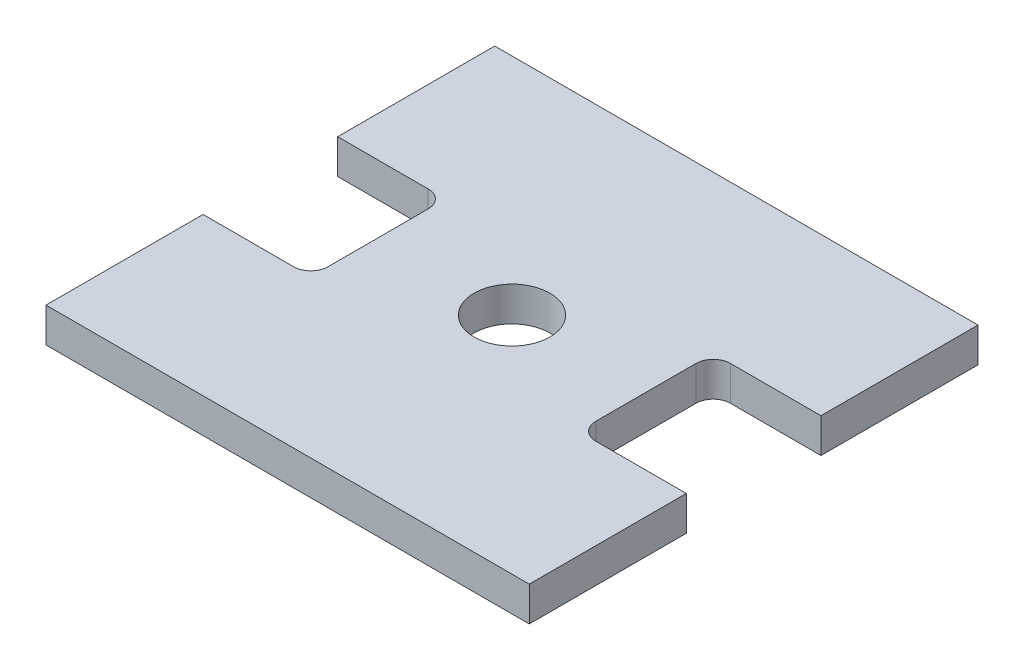
SolidWorks part; units mm, degrees
ref_plane "Спереди" through (0, 0, 0) normal (0, 0, 1) x (1, 0, 0)
ref_plane "Сверху" through (0, 0, 0) normal (0, 1, 0) x (1, 0, 0)
ref_plane "Справа" through (0, 0, 0) normal (1, 0, 0) x (0, 0, -1)
sketch "Эскиз1" plane through (0, 0, 0) normal (0, 1, 0) x (1, 0, 0)
  line L0 (-34.1763, -81.9426) -> (105.8237, 48.0574) construction
  line L1 (-34.1763, 48.0574) -> (105.8237, 48.0574)
  line L2 (-34.1763, 48.0574) -> (-34.1763, 2.5621)
  line L3 (-34.1763, -81.9426) -> (105.8237, -81.9426)
  line L4 (105.8237, 48.0574) -> (105.8237, 2.5621)
  line L5 (-34.1763, 48.0574) -> (105.8237, -81.9426) construction
  line L6 (35.8237, -16.9426) -> (135.9029, -16.9426) construction
  line L7 (-34.1763, -36.4474) -> (-7.9539, -36.4474)
  line L8 (-2.9539, -2.4379) -> (-2.9539, -31.4474)
  line L9 (-34.1763, 2.5621) -> (-7.9539, 2.5621)
  line L10 (-34.1763, -36.4474) -> (-34.1763, -81.9426)
  line L11 (35.8237, -16.9426) -> (35.8237, 51.4154) construction
  line L12 (105.8237, -36.4474) -> (79.6013, -36.4474)
  line L13 (74.6013, -2.4379) -> (74.6013, -31.4474)
  line L14 (105.8237, 2.5621) -> (79.6013, 2.5621)
  line L15 (105.8237, -36.4474) -> (105.8237, -81.9426)
  circle A0 centre (35.8237, -16.9426) radius 11
  arc A1 (-2.9539, -2.4379) -> (-7.9539, 2.5621) centre (-7.9539, -2.4379) ccw
  arc A2 (-7.9539, -36.4474) -> (-2.9539, -31.4474) centre (-7.9539, -31.4474) ccw
  arc A3 (79.6013, -36.4474) -> (74.6013, -31.4474) centre (79.6013, -31.4474) cw
  arc A4 (74.6013, -2.4379) -> (79.6013, 2.5621) centre (79.6013, -2.4379) cw
  point P12 (-2.9539, 2.5621)
  point P15 (-1.9271, -16.9426)
  point P21 (-2.9539, -36.4474)
  dimension "D1" = 5
  dimension "D2" = 65
  dimension "D3" = 70
extrude "Вытянуть1" add sketch "Эскиз1" along normal blind 10
